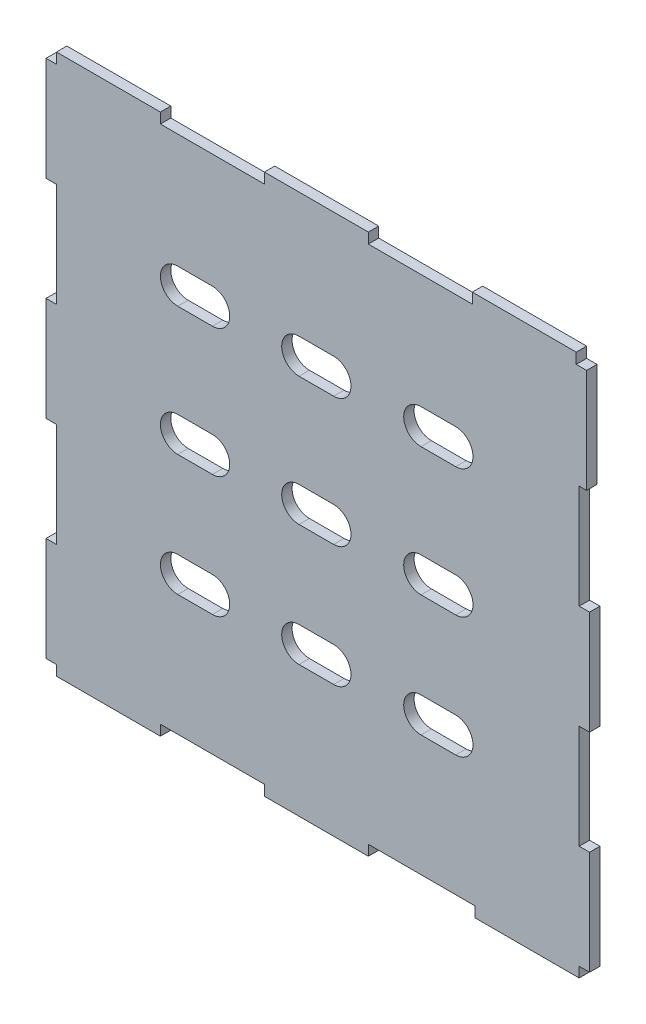
SolidWorks part; units mm, degrees
material "Pinho"
ref_plane "Plano frontal" through (0, 0, 0) normal (0, 0, 1) x (1, 0, 0)
ref_plane "Plano superior" through (0, 0, 0) normal (0, 1, 0) x (1, 0, 0)
ref_plane "Plano direito" through (0, 0, 0) normal (1, 0, 0) x (0, 0, -1)
sketch "Esboço1" plane through (0, 0, 0) normal (0, 0, 1) x (1, 0, 0)
  line L0 (-80.1414, 21.254) -> (-83.1414, 21.254)
  line L1 (40.7004, -128.6775) -> (9.8586, -128.6775)
  line L3 (39.8586, 21.3225) -> (9.8586, 21.3225)
  line L6 (-20.1414, 21.3225) -> (-50.1414, 21.3225)
  line L15 (72.8586, 21.254) -> (72.8586, -8.746)
  line L25 (-80.1414, 21.254) -> (-80.1414, 24.3225)
  line L26 (69.8586, 21.254) -> (72.8586, 21.254)
  line L30 (70.7004, -128.746) -> (73.7004, -128.746)
  line L34 (-80.1414, 24.3225) -> (-50.1414, 24.3225)
  line L35 (-50.1414, 21.3225) -> (-50.1414, 24.3225)
  line L37 (69.8586, 21.254) -> (69.8586, 24.3225)
  line L38 (69.8586, 24.3225) -> (39.8586, 24.3225)
  line L39 (39.8586, 21.3225) -> (39.8586, 24.3225)
  line L41 (-20.1414, 21.3225) -> (-20.1414, 24.3225)
  line L42 (-20.1414, 24.3225) -> (9.8586, 24.3225)
  line L43 (9.8586, 21.3225) -> (9.8586, 24.3225)
  line L44 (-20.1414, -128.6775) -> (-50.1414, -128.6775)
  line L46 (-20.1414, -128.6775) -> (-20.1414, -131.6775)
  line L47 (-20.1414, -131.6775) -> (9.8586, -131.6775)
  line L48 (9.8586, -128.6775) -> (9.8586, -131.6775)
  line L49 (72.8586, -8.746) -> (70.7004, -8.746)
  line L50 (70.7004, -8.746) -> (70.7004, -38.746)
  line L52 (-80.1414, -128.746) -> (-80.1414, -131.6775)
  line L53 (-80.1414, -131.6775) -> (-50.1414, -131.6775)
  line L54 (-50.1414, -128.6775) -> (-50.1414, -131.6775)
  line L56 (70.7004, -128.746) -> (70.7004, -131.6775)
  line L57 (70.7004, -131.6775) -> (40.7004, -131.6775)
  line L58 (40.7004, -128.6775) -> (40.7004, -131.6775)
  line L59 (70.7004, -38.746) -> (73.7004, -38.746)
  line L60 (73.7004, -38.746) -> (73.7004, -68.746)
  line L61 (73.7004, -68.746) -> (70.7004, -68.746)
  line L62 (70.7004, -68.746) -> (70.7004, -98.746)
  line L63 (70.7004, -98.746) -> (73.7004, -98.746)
  line L64 (73.7004, -98.746) -> (73.7004, -128.746)
  line L65 (-80.1414, -128.746) -> (-83.1414, -128.746)
  line L66 (-83.1414, -128.746) -> (-83.1414, -98.746)
  line L67 (-83.1414, -98.746) -> (-80.1414, -98.746)
  line L68 (-80.1414, -98.746) -> (-80.1414, -68.746)
  line L69 (-80.1414, -68.746) -> (-83.1414, -68.746)
  line L70 (-83.1414, -68.746) -> (-83.1414, -38.746)
  line L71 (-83.1414, -38.746) -> (-80.1414, -38.746)
  line L72 (-80.1414, -38.746) -> (-80.1414, -8.746)
  line L73 (-80.1414, -8.746) -> (-83.1414, -8.746)
  line L74 (-83.1414, -8.746) -> (-83.1414, 21.254)
  line L75 (-5.1414, 24.3225) -> (-5.1414, -131.6775) construction
  line L76 (73.7004, -53.746) -> (-83.1414, -53.746) construction
  line L77 (-5.1414, -53.6775) -> (29.8586, -53.746) construction
  line L78 (-5.1414, -53.6775) -> (-40.1414, -53.746) construction
  line L79 (29.8586, -128.6775) -> (29.8586, 21.3225) construction
  line L80 (-40.1414, 21.3225) -> (-40.1414, -128.6775) construction
  line L81 (70.7004, -16.6992) -> (-80.1414, -16.6992) construction
  line L82 (70.7004, -88.746) -> (-80.1414, -88.746) construction
  line L83 (35.0666, -16.6992) -> (25.0666, -16.6992) construction
  line L84 (35.0666, -21.6992) -> (25.0666, -21.6992)
  line L85 (35.0666, -11.6992) -> (25.0666, -11.6992)
  line L86 (-0.1414, -16.6992) -> (-10.1414, -16.6992) construction
  line L87 (-0.1414, -21.6992) -> (-10.1414, -21.6992)
  line L88 (-0.1414, -11.6992) -> (-10.1414, -11.6992)
  line L89 (-35.1414, -16.6992) -> (-45.1414, -16.6992) construction
  line L90 (-35.1414, -21.6992) -> (-45.1414, -21.6992)
  line L91 (-35.1414, -11.6992) -> (-45.1414, -11.6992)
  line L92 (35.0666, -53.746) -> (25.0666, -53.746) construction
  line L93 (35.0666, -58.746) -> (25.0666, -58.746)
  line L94 (35.0666, -48.746) -> (25.0666, -48.746)
  line L95 (-0.1414, -53.746) -> (-10.1414, -53.746) construction
  line L96 (-0.1414, -58.746) -> (-10.1414, -58.746)
  line L97 (-0.1414, -48.746) -> (-10.1414, -48.746)
  line L98 (-35.1414, -53.746) -> (-45.1414, -53.746) construction
  line L99 (-35.1414, -58.746) -> (-45.1414, -58.746)
  line L100 (-35.1414, -48.746) -> (-45.1414, -48.746)
  line L101 (35.0666, -88.746) -> (25.0666, -88.746) construction
  line L102 (35.0666, -93.746) -> (25.0666, -93.746)
  line L103 (35.0666, -83.746) -> (25.0666, -83.746)
  line L104 (-0.1414, -88.746) -> (-10.1414, -88.746) construction
  line L105 (-0.1414, -93.746) -> (-10.1414, -93.746)
  line L106 (-0.1414, -83.746) -> (-10.1414, -83.746)
  line L107 (-35.1414, -88.746) -> (-45.1414, -88.746) construction
  line L108 (-35.1414, -93.746) -> (-45.1414, -93.746)
  line L109 (-35.1414, -83.746) -> (-45.1414, -83.746)
  arc A0 (35.0666, -21.6992) -> (35.0666, -11.6992) centre (35.0666, -16.6992) ccw
  arc A1 (25.0666, -11.6992) -> (25.0666, -21.6992) centre (25.0666, -16.6992) ccw
  arc A2 (-0.1414, -21.6992) -> (-0.1414, -11.6992) centre (-0.1414, -16.6992) ccw
  arc A3 (-10.1414, -11.6992) -> (-10.1414, -21.6992) centre (-10.1414, -16.6992) ccw
  arc A4 (-35.1414, -21.6992) -> (-35.1414, -11.6992) centre (-35.1414, -16.6992) ccw
  arc A5 (-45.1414, -11.6992) -> (-45.1414, -21.6992) centre (-45.1414, -16.6992) ccw
  arc A6 (35.0666, -58.746) -> (35.0666, -48.746) centre (35.0666, -53.746) ccw
  arc A7 (25.0666, -48.746) -> (25.0666, -58.746) centre (25.0666, -53.746) ccw
  arc A8 (-0.1414, -58.746) -> (-0.1414, -48.746) centre (-0.1414, -53.746) ccw
  arc A9 (-10.1414, -48.746) -> (-10.1414, -58.746) centre (-10.1414, -53.746) ccw
  arc A10 (-35.1414, -58.746) -> (-35.1414, -48.746) centre (-35.1414, -53.746) ccw
  arc A11 (-45.1414, -48.746) -> (-45.1414, -58.746) centre (-45.1414, -53.746) ccw
  arc A12 (35.0666, -93.746) -> (35.0666, -83.746) centre (35.0666, -88.746) ccw
  arc A13 (25.0666, -83.746) -> (25.0666, -93.746) centre (25.0666, -88.746) ccw
  arc A14 (-0.1414, -93.746) -> (-0.1414, -83.746) centre (-0.1414, -88.746) ccw
  arc A15 (-10.1414, -83.746) -> (-10.1414, -93.746) centre (-10.1414, -88.746) ccw
  arc A16 (-35.1414, -93.746) -> (-35.1414, -83.746) centre (-35.1414, -88.746) ccw
  arc A17 (-45.1414, -83.746) -> (-45.1414, -93.746) centre (-45.1414, -88.746) ccw
  point P61 (30.0666, -16.6992)
  point P68 (-5.1414, -16.6992)
  point P73 (-40.1414, -16.6992)
  point P82 (30.0666, -53.746)
  point P87 (-5.1414, -53.746)
  point P94 (-40.1414, -53.746)
  point P101 (30.0666, -88.746)
  point P108 (-5.1414, -88.746)
  point P115 (-40.1414, -88.746)
  dimension "D28" = 5
  dimension "D29" = 5
  dimension "D30" = 5
  dimension "D33" = 5
  dimension "D12" = 5
  dimension "D14" = 5
  dimension "D31" = 5
  dimension "D32" = 5
  dimension "D34" = 5
  dimension "D2" = 150
  dimension "D3" = 150
  dimension "D4" = 30
  dimension "D5" = 30
  dimension "D6" = 3
  dimension "D7" = 35
  dimension "D8" = 35
  dimension "D9" = 35
  dimension "D10" = 37.0467
  dimension "D11" = 10
  dimension "D13" = 10
  dimension "D15" = 10
  dimension "D16" = 30
  dimension "D17" = 30
  dimension "D18" = 30
  dimension "D19" = 3
  dimension "D20" = 3
  dimension "D21" = 3
  dimension "D22" = 30
  dimension "D23" = 30
  dimension "D24" = 30
  dimension "D25" = 3
  dimension "D26" = 3
  dimension "D27" = 3
  dimension "D35" = 3
  dimension "D36" = 3
extrude "Ressalto-extrusão1" add sketch "Esboço1" along normal blind 3
